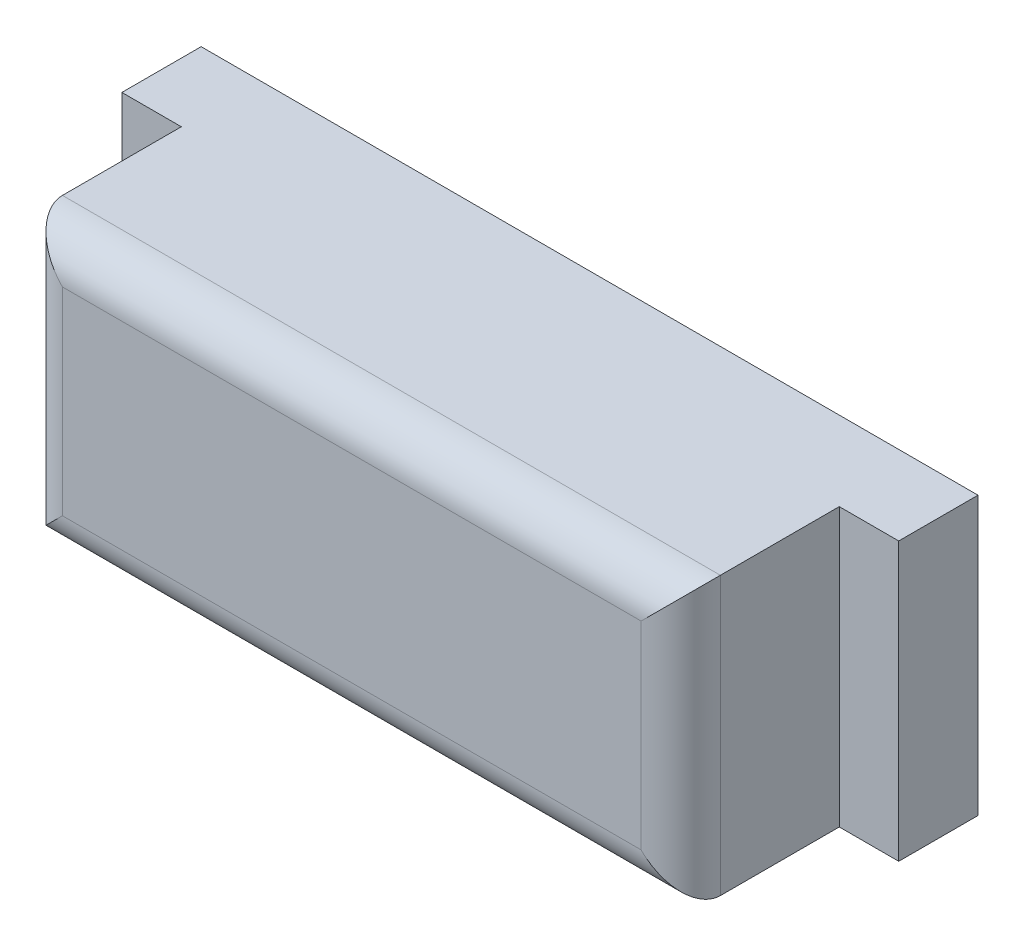
SolidWorks part; units mm, degrees
ref_plane "前视基准面" through (0, 0, 0) normal (0, 0, 1) x (1, 0, 0)
ref_plane "上视基准面" through (0, 0, 0) normal (0, 1, 0) x (1, 0, 0)
ref_plane "右视基准面" through (0, 0, 0) normal (1, 0, 0) x (0, 0, -1)
sketch "草图1" plane through (0, 0, 0) normal (0, 0, 1) x (1, 0, 0)
  line L1 (-4.9, 1.75) -> (4.9, 1.75)
  line L2 (-4.9, 1.75) -> (-4.9, -1.75)
  line L3 (-4.9, -1.75) -> (4.9, -1.75)
  line L4 (4.9, 1.75) -> (4.9, -1.75)
  line L5 (-4.9, 1.75) -> (4.9, -1.75) construction
  line L6 (-4.9, -1.75) -> (4.9, 1.75) construction
  point P0 (0, 0)
  dimension "D1" = 9.8
  dimension "D2" = 3.5
extrude "凸台-拉伸1" add sketch "草图1" along normal blind 1
sketch "草图2" plane through (0, 0, 1) normal (0, 0, 1) x (1, 0, 0)
  line L1 (-4.15, 1.75) -> (4.15, 1.75)
  line L2 (-4.15, 1.75) -> (-4.15, -1.75)
  line L3 (-4.15, -1.75) -> (4.15, -1.75)
  line L4 (4.15, 1.75) -> (4.15, -1.75)
  line L5 (-4.15, 1.75) -> (4.15, -1.75) construction
  line L6 (-4.15, -1.75) -> (4.15, 1.75) construction
  point P0 (0, 0)
  dimension "D1" = 8.3
  dimension "D2" = 3.5
extrude "凸台-拉伸2" add sketch "草图2" along normal blind 2
fillet "圆角2" radius 0.5 4 edges at (-4.15, 0, 3) (0, -1.75, 3) (0, 1.75, 3) (4.15, 0, 3)
